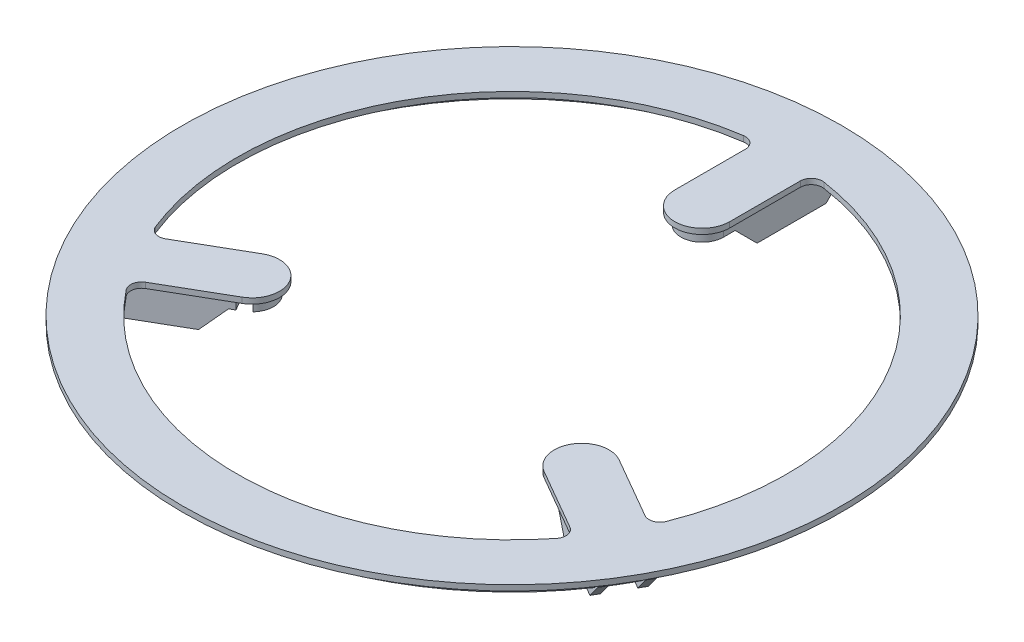
SolidWorks part; units mm, degrees
ref_plane "Front Plane" through (0, 0, 0) normal (0, 0, 1) x (1, 0, 0)
ref_plane "Top Plane" through (0, 0, 0) normal (0, 1, 0) x (1, 0, 0)
ref_plane "Right Plane" through (0, 0, 0) normal (1, 0, 0) x (0, 0, -1)
sketch "Sketch1" plane through (0, 0, 0) normal (0, 1, 0) x (1, 0, 0)
  line L0 (0, 86.6025) -> (75, -43.3013) construction
  line L1 (0, 86.6025) -> (-75, -43.3013) construction
  line L2 (-75, -43.3013) -> (75, -43.3013) construction
  line L3 (-12.5, 86.6004) -> (-12.5064, 124.3728)
  line L4 (12.5, 86.6004) -> (12.5064, 124.3728)
  line L5 (81.2482, -32.4749) -> (113.9632, -51.3555)
  line L6 (68.7482, -54.1255) -> (101.4568, -73.0173)
  line L7 (-68.7482, -54.1255) -> (-101.4568, -73.0173)
  line L8 (-81.2482, -32.4749) -> (-113.9632, -51.3555)
  circle A0 centre (0, 0) radius 150
  arc A1 (-12.5064, 124.3728) -> (-113.9632, -51.3555) centre (0, 0) ccw
  circle A2 centre (0, 0) radius 86.6025 construction
  arc A3 (-12.5, 86.6004) -> (12.5, 86.6004) centre (0, 86.6025) ccw
  arc A4 (81.2482, -32.4749) -> (68.7482, -54.1255) centre (75, -43.3013) ccw
  arc A5 (-68.7482, -54.1255) -> (-81.2482, -32.4749) centre (-75, -43.3013) ccw
  arc A6 (113.9632, -51.3555) -> (12.5064, 124.3728) centre (0, 0) ccw
  arc A7 (-101.4568, -73.0173) -> (101.4568, -73.0173) centre (0, 0) ccw
  dimension "D1" = 300
  dimension "D2" = 250
  dimension "D3" = 150
  dimension "D4" = 25
  dimension "D5" = 3
extrude "Boss-Extrude1" add sketch "Sketch1" along normal blind 2.5
sketch "Sketch2" plane through (0, 0, 0) normal (0, -1, 0) x (1, 0, 0)
  line L0 (-76.0413, 46.048) -> (-72.1008, 43.7738)
  line L1 (-113.9632, 51.3555) -> (-81.2482, 32.4749) construction
  line L2 (77.8994, 42.8297) -> (73.9596, 40.5542)
  line L3 (-1.8581, -88.8777) -> (-1.8589, -84.328)
  arc A0 (-76.0413, 46.048) -> (-72.1008, 43.7738) centre (-75, 43.3013) ccw
  arc A3 (77.8994, 42.8297) -> (73.9596, 40.5542) centre (75, 43.3013) ccw
  arc A4 (-1.8581, -88.8777) -> (-1.8589, -84.328) centre (0, -86.6025) ccw
  dimension "D2" = 5.875
  dimension "D1" = 3
extrude "Boss-Extrude2" add sketch "Sketch2" along normal blind 6
sketch "Sketch3" plane through (0, 0, 0) normal (0, -1, 0) x (1, 0, 0)
  line L0 (77.7745, 42.7575) -> (77.8994, 42.8297)
  line L1 (-72.1008, 43.7738) -> (-76.0413, 46.048)
  line L3 (73.9596, 40.5542) -> (77.8994, 42.8297)
  line L6 (-1.8589, -84.328) -> (-1.8581, -88.8777)
  circle A0 centre (-75, 43.3013) radius 2.9375
  arc A1 (-76.0413, 46.048) -> (-72.1008, 43.7738) centre (-75, 43.3013) ccw
  arc A2 (-76.0413, 46.048) -> (-72.1008, 43.7738) centre (-75, 43.3013) ccw
  circle A3 centre (75, 43.3013) radius 2.9375
  arc A4 (77.8994, 42.8297) -> (73.9596, 40.5542) centre (75, 43.3013) ccw
  arc A5 (77.8994, 42.8297) -> (73.9596, 40.5542) centre (75, 43.3013) ccw
  circle A7 centre (0, -86.6025) radius 2.9375
  arc A8 (-1.8581, -88.8777) -> (-1.8589, -84.328) centre (0, -86.6025) ccw
  arc A9 (-1.8581, -88.8777) -> (-1.8589, -84.328) centre (0, -86.6025) ccw
  dimension "D2" = 0
  dimension "D3" = 0
  dimension "D1" = 0
extrude "Boss-Extrude3" add sketch "Sketch3" along normal blind 1 contours A0 | A3 | A7
sketch "Sketch4" plane through (0, 0, 0) normal (0, -1, 0) x (1, 0, 0)
  line L0 (-128.8923, 63.1942) -> (-84.3899, 37.5008)
  line L1 (-128.8923, 63.1942) -> (-127.1423, 66.2253)
  line L2 (-84.3899, 37.5008) -> (-82.6399, 40.5319)
  line L3 (-127.1423, 66.2253) -> (-82.6399, 40.5319)
  line L4 (-120.924, 76.9958) -> (-76.4216, 51.3023)
  line L5 (-120.924, 76.9958) -> (-119.174, 80.0269)
  line L6 (-76.4216, 51.3023) -> (-74.6716, 54.3334)
  line L7 (-119.174, 80.0269) -> (-74.6716, 54.3334)
  line L8 (-75, 43.3013) -> (43226.2702, -24956.6987) construction
  circle A1 centre (0, 0) radius 150
  circle A2 centre (0, 0) radius 150
  dimension "D2" = 3.5
  dimension "D1" = 0
extrude "Boss-Extrude4" add sketch "Sketch4" along normal blind 15 contours L0 L1 L3 L2 | L4 L5 L7 L6
chamfer "Chamfer1" distance 10 angle 45 4 edges at (-83.5149, -15, 39.0163) (-75.5466, -15, 52.8179) (-120.049, -15, 78.5113) (-128.0173, -15, 64.7098)
sketch "Sketch5" plane through (0, 0, 0) normal (0, -1, 0) x (1, 0, 0)
  line L0 (0, 0) -> (-133.0315, 22.9698) construction
  line L1 (0, 0) -> (-46.6234, -126.6936) construction
  line L2 (0, 0) -> (43301.2702, 25000) construction
  circle A0 centre (-75, 43.3013) radius 5.5 construction
  circle A1 centre (0, 0) radius 140
  circle A2 centre (0, 0) radius 135
  arc A3 (-137.9586, 23.8205) -> (-48.3502, -131.3859) centre (0, 0) ccw
  arc A6 (-133.0315, 22.9698) -> (-46.6234, -126.6936) centre (0, 0) ccw
  dimension "D1" = 11
extrude "Boss-Extrude5" add sketch "Sketch5" along normal blind 7.5 contours A1 | A2
pattern_circular "CirPattern1" count 3 over 360 about axis through (0, 0, 0) along (0, 1, 0) of "Boss-Extrude4", "Chamfer1"
sketch "Sketch6" plane through (0, 0, 0) normal (0, -1, 0) x (1, 0, 0)
  line L0 (-111.7509, 75.7412) -> (-74.6716, 54.3334) construction
  line L1 (-74.6716, 54.3334) -> (-70.1408, 51.7176)
  line L2 (-83.3318, 59.3334) -> (-74.6716, 54.3334) construction
  line L3 (-84.3899, 37.5008) -> (-79.8592, 34.8849)
  line L4 (-121.4693, 58.9085) -> (-84.3899, 37.5008) construction
  line L5 (-74.6716, 54.3334) -> (-75.4357, 53.0098)
  line L6 (-76.4216, 51.3023) -> (-74.6716, 54.3334) construction
  line L8 (-83.6257, 38.8243) -> (-84.3899, 37.5008)
  circle A0 centre (-75, 43.3013) radius 6.2638
  arc A1 (-75.4357, 53.0098) -> (-83.6257, 38.8243) centre (-75, 43.3013) ccw
  arc A2 (-79.8592, 34.8849) -> (-70.1408, 51.7176) centre (-75, 43.3013) ccw
extrude "Boss-Extrude6" add sketch "Sketch6" along normal blind 5
sketch "Sketch7" plane through (0.9363, 0, 1.6224) normal (0.4999, 0, 0.8661) x (0.8661, 0, -0.4999)
  line L0 (-89.3774, -1) -> (-89.3774, -6.5)
  line L1 (-89.3774, -6.5) -> (-83.8277, -6.5)
  line L2 (-83.8277, -6.5) -> (-83.8277, -1)
  line L3 (-89.3774, -1) -> (-83.8277, -1)
  line L4 (-84.3277, -6) -> (-84.3277, -1)
  line L5 (-84.3277, -1) -> (-88.8774, -1)
  line L6 (-88.8774, -1) -> (-88.8774, -6)
  line L7 (-88.8774, -6) -> (-84.3277, -6)
  line L9 (-84.3277, -1) -> (-88.8774, -1)
  dimension "D1" = 0
extrude "Cut-Extrude2" cut sketch "Sketch7" along normal up to next contours L3 L2 L1 L0
pattern_circular "CirPattern2" count 3 over 360 about axis through (0, 0, 0) along (0, 1, 0) of "Boss-Extrude6", "Cut-Extrude2"
fillet "Fillet1" radius 5 6 edges at (101.4568, 1.25, 73.0173) (113.9632, 1.25, 51.3555) (-113.9632, 1.25, 51.3555) (-101.4568, 1.25, 73.0173) (12.5064, 1.25, -124.3728) (-12.5064, 1.25, -124.3728)
